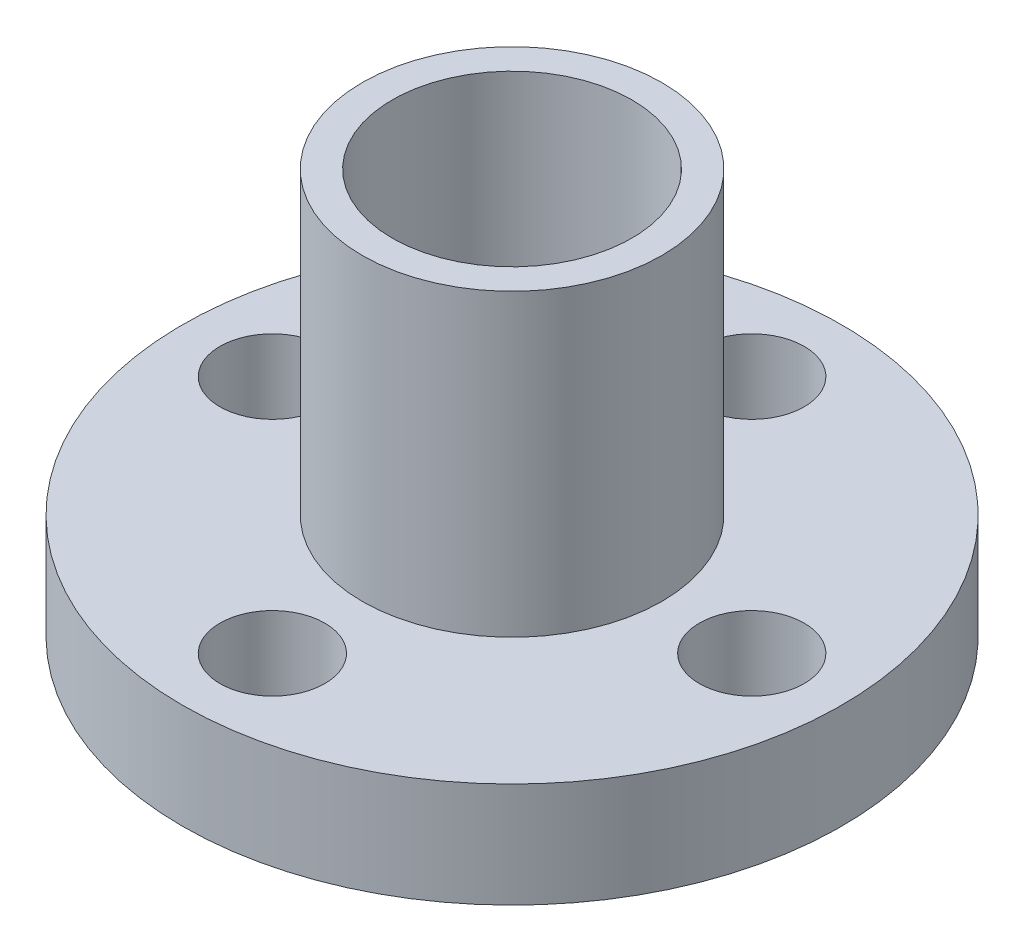
SolidWorks part; units mm, degrees
material "Brass"
ref_plane "Ebene vorne" through (0, 0, 0) normal (0, 0, 1) x (1, 0, 0)
ref_plane "Ebene oben" through (0, 0, 0) normal (0, 1, 0) x (1, 0, 0)
ref_plane "Ebene rechts" through (0, 0, 0) normal (1, 0, 0) x (0, 0, -1)
sketch "Sketch1" plane through (0, 0, 0) normal (1, 0, 0) x (0, 0, -1)
  line L0 (0, 28.7304) -> (0, 0)
  line L1 (0, 0) -> (1, 0)
  line L2 (1, 0) -> (1, 1.5)
  line L3 (1, 1.5) -> (7, 1.5)
  line L4 (7, 1.5) -> (7, 5)
  line L5 (7, 5) -> (1, 5)
  line L6 (1, 5) -> (1, 15)
  line L7 (1, 15) -> (0, 15)
  line L8 (0, 15) -> (0, 28.7304)
  line L9 (0, 15) -> (-4, 15)
  line L10 (-4, 15) -> (-4, 0)
  dimension "D1" = 4
  dimension "D2" = 5
  dimension "D3" = 11
  dimension "D4" = 5
  dimension "D5" = 15
  dimension "D6" = 15
  dimension "D7" = 10
  dimension "D8" = 3.5
revolve "Revolve1" add sketch "Sketch1" angle 360 about L10
sketch "Sketch2" plane through (0, 1.5, 0) normal (0, -1, 0) x (1, 0, 0)
  line L0 (0, 4) -> (0, -4)
  circle A1 centre (0, -4) radius 1.75
  circle A2 centre (-8, 4) radius 1.75
  circle A3 centre (0, 12) radius 1.75
  circle A4 centre (8, 4) radius 1.75
  point P14 (0, 4)
  dimension "D1" = 8
  dimension "D2" = 4
extrude "Cut-Extrude1" cut sketch "Sketch2" against normal through all
